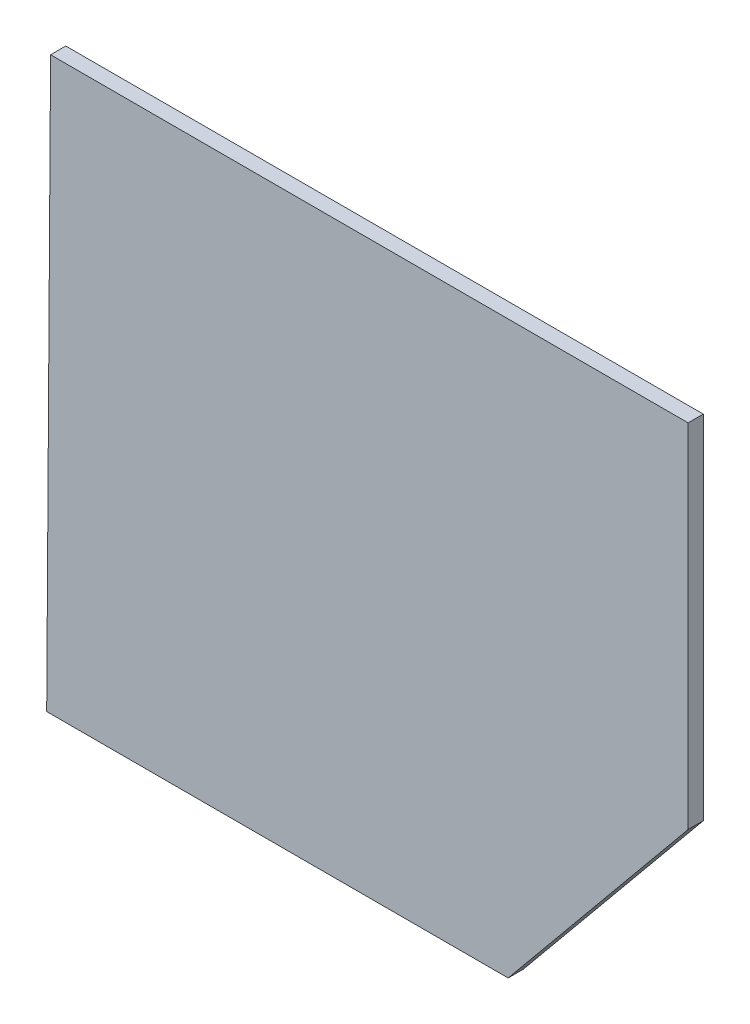
SolidWorks part; units mm, degrees
material "ASTM A500 Grade B"
ref_plane "Front Plane" through (0, 0, 0) normal (0, 0, 1) x (1, 0, 0)
ref_plane "Top Plane" through (0, 0, 0) normal (0, 1, 0) x (1, 0, 0)
ref_plane "Right Plane" through (0, 0, 0) normal (1, 0, 0) x (0, 0, -1)
sketch "Sketch1" plane through (0, 0, 0) normal (0, 0, 1) x (1, 0, 0)
  line L0 (-1993.5728, -105.0897) -> (-1955.928, -59.3697)
  line L1 (-1955.928, -59.3697) -> (-1955.928, 14.2903)
  line L2 (-1955.928, 14.2903) -> (-2089.278, 14.2903)
  line L3 (-2089.278, 14.2903) -> (-2090.0928, -105.0897)
  line L5 (-2090.0928, -105.0897) -> (-1993.5728, -105.0897)
  dimension "D1" = 96.52
  dimension "D2" = 73.66
  dimension "D3" = 133.35
  dimension "D4" = 119.38
extrude "Boss-Extrude1" add sketch "Sketch1" along normal blind 3.175
